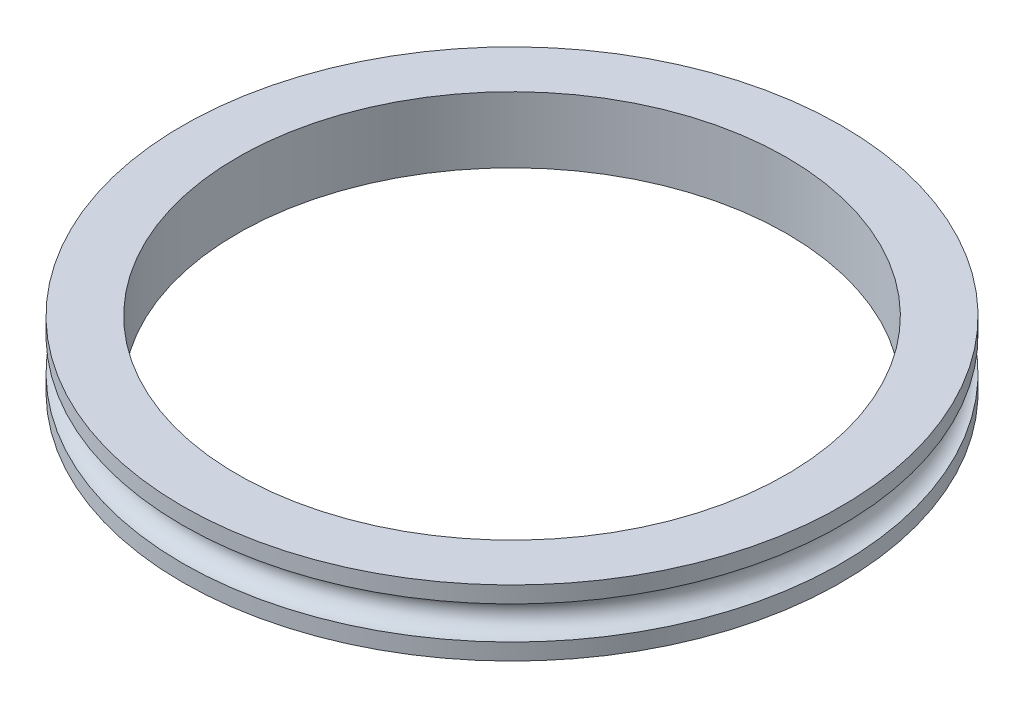
SolidWorks part; units mm, degrees
ref_plane "Alzado" through (0, 0, 0) normal (0, 0, 1) x (1, 0, 0)
ref_plane "Planta" through (0, 0, 0) normal (0, 1, 0) x (1, 0, 0)
ref_plane "Vista lateral" through (0, 0, 0) normal (1, 0, 0) x (0, 0, -1)
sketch "Croquis1" plane through (0, 0, 0) normal (0, 1, 0) x (1, 0, 0)
  circle A0 centre (0, 0) radius 15
  dimension "D1" = 30
extrude "Saliente-Extruir1" add sketch "Croquis1" along normal mid plane 3
ref_axis "Eje1" through (0, 1.5, 0) along (0, -1, 0)
sketch "Croquis2" plane through (0, 0, 0) normal (1, 0, 0) x (0, 0, -1)
  line L0 (15, -1.5) -> (15, 1.5) construction
  circle A0 centre (15, 0) radius 0.75
  dimension "D1" = 1.5
revolve "Cortar-Revolución1" cut sketch "Croquis2" angle 360 about axis through (0, 1.5, 0) along (0, -1, 0)
sketch "Croquis4" plane through (0, -1.5, 0) normal (0, -1, 0) x (1, 0, 0)
  circle A0 centre (0, 0) radius 12.5
  dimension "D1" = 25
extrude "Cortar-Extruir1" cut sketch "Croquis4" against normal through all
